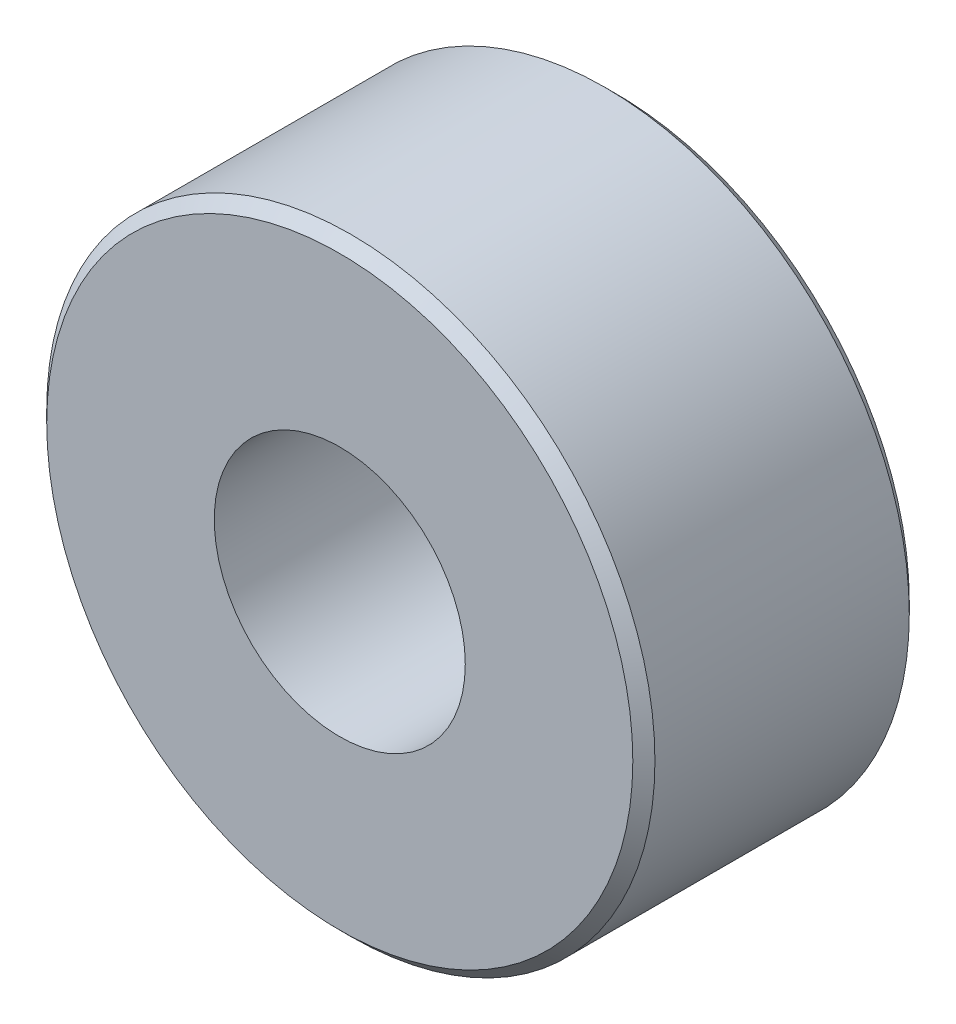
SolidWorks part; units mm, degrees
ref_plane "Front Plane" through (0, 0, 0) normal (0, 0, 1) x (1, 0, 0)
ref_plane "Top Plane" through (0, 0, 0) normal (0, 1, 0) x (1, 0, 0)
ref_plane "Right Plane" through (0, 0, 0) normal (1, 0, 0) x (0, 0, -1)
sketch "Sketch1" plane through (0, 0, 0) normal (0, 0, 1) x (1, 0, 0)
  circle A0 centre (0, 0) radius 27.5
  dimension "D1" = 55
extrude "Boss-Extrude1" add sketch "Sketch1" along normal mid plane 25
sketch "Sketch2" plane through (0, 0, 0) normal (0, 0, 1) x (1, 0, 0)
  circle A0 centre (0, 0) radius 11.35
  dimension "D1" = 22.7
extrude "Cut-Extrude1" cut sketch "Sketch2" against normal through all both and the other way through all
chamfer "Chamfer1" distance 1 angle 45 2 edges at (27.5, 0, -12.5) (27.5, 0, 12.5)
